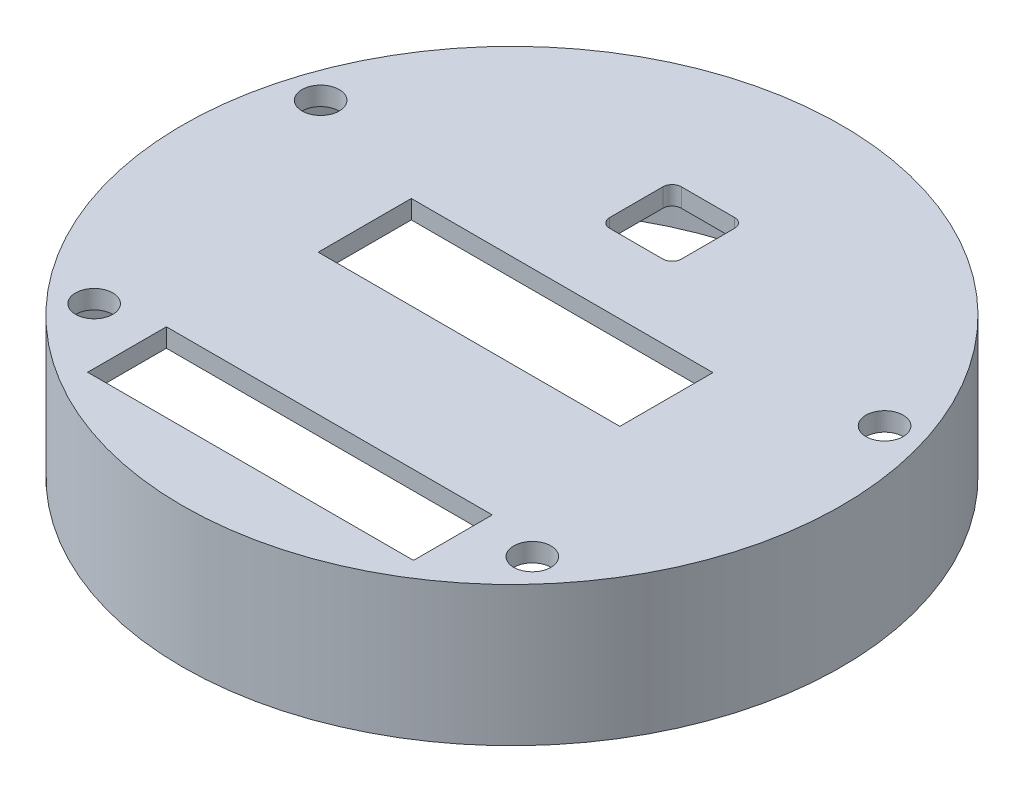
SolidWorks part; units mm, degrees
material "PBT General Purpose"
ref_plane "Front Plane" through (0, 0, 0) normal (0, 0, 1) x (1, 0, 0)
ref_plane "Top Plane" through (0, 0, 0) normal (0, 1, 0) x (1, 0, 0)
ref_plane "Right Plane" through (0, 0, 0) normal (1, 0, 0) x (0, 0, -1)
sketch "Sketch1" plane through (0, 0, 0) normal (0, 1, 0) x (1, 0, 0)
  circle A0 centre (0, 0) radius 175
extrude "Boss-Extrude1" add sketch "Sketch1" along normal blind 10
sketch "Sketch2" plane through (0, 10, 0) normal (0, 1, 0) x (1, 0, 0)
  circle A0 centre (-151.4263, 48.6932) radius 1
  circle A1 centre (0, 0) radius 175
  circle A2 centre (0, 0) radius 175
  circle A6 centre (-151.4263, 48.6932) radius 10
  circle A7 centre (151.4263, 48.6932) radius 10
  circle A8 centre (117.6657, -106.7049) radius 10
  circle A9 centre (-117.6657, -106.7049) radius 10
  dimension "D1" = 0
sketch "Sketch3" plane through (0, 0, 0) normal (0, -1, 0) x (1, 0, 0)
  line L1 (-81.4238, -27.3789) -> (80.5762, -27.3789)
  line L2 (-81.4238, -27.3789) -> (-81.4238, 22.6211)
  line L3 (-81.4238, 22.6211) -> (80.5762, 22.6211)
  line L4 (80.5762, -27.3789) -> (80.5762, 22.6211)
  line L5 (-87.5, 98.0764) -> (87.5, 98.0764)
  line L6 (-87.5, 98.0764) -> (-87.5, 140.3737)
  line L7 (-87.5, 140.3737) -> (87.5, 140.3737)
  line L8 (87.5, 98.0764) -> (87.5, 140.3737)
  circle A0 centre (-117.6657, 106.7049) radius 10
  circle A1 centre (117.6657, 106.7049) radius 10
  circle A2 centre (151.4263, -48.6932) radius 10
  circle A3 centre (-151.4263, -48.6932) radius 10
extrude "Cut-Extrude2" cut sketch "Sketch3" against normal blind 10
sketch "Sketch4" plane through (0, 0, 0) normal (0, -1, 0) x (1, 0, 0)
  line L0 (-14.298, -66.7471) -> (14.298, -66.7471)
  line L2 (19.295, -71.7441) -> (19.295, -100.3402)
  line L4 (14.2993, -105.3371) -> (-14.298, -105.3371)
  line L6 (-19.295, -71.7441) -> (-19.295, -100.3414)
  arc A0 (-14.298, -66.7471) -> (-19.295, -71.7441) centre (-14.298, -71.7441) ccw
  arc A1 (-19.295, -100.3414) -> (-14.298, -105.3371) centre (-14.2993, -100.3414) ccw
  arc A2 (14.298, -66.7471) -> (19.295, -71.7441) centre (14.298, -71.7441) cw
  arc A3 (19.295, -100.3402) -> (14.2993, -105.3371) centre (14.2993, -100.3414) cw
extrude "Cut-Extrude3" cut sketch "Sketch4" against normal blind 10
sketch "Sketch5" plane through (0, 10, 0) normal (0, 1, 0) x (1, 0, 0)
  circle A0 centre (0, 0) radius 175
  circle A1 centre (0, 0) radius 177
extrude "Boss-Extrude2" add sketch "Sketch5" against normal up to surface (75 mm away)
